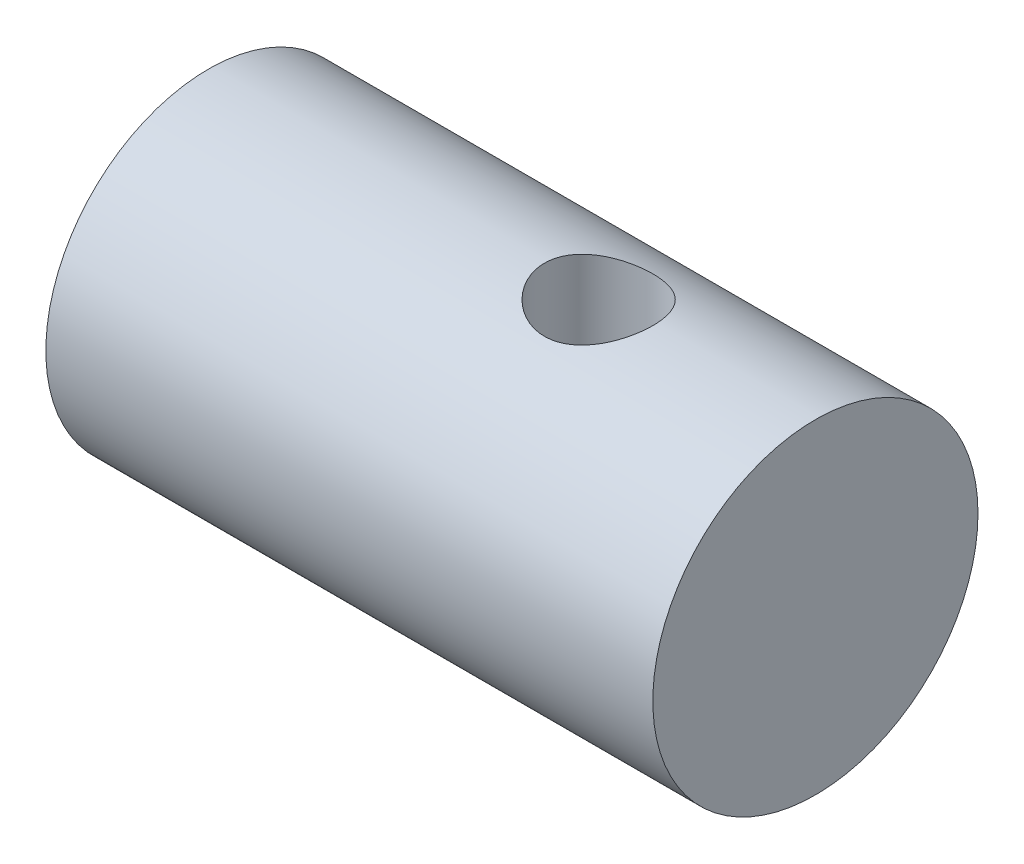
SolidWorks part; units mm, degrees
other "Preload Motor Output Shaft"
ref_plane "Front Plane" through (0, 0, 0) normal (0, 0, 1) x (1, 0, 0)
ref_plane "Top Plane" through (0, 0, 0) normal (0, 1, 0) x (1, 0, 0)
ref_plane "Right Plane" through (0, 0, 0) normal (1, 0, 0) x (0, 0, -1)
sketch3d "Finished shaft allocation sketch datum points"
  point P0 (-9.2, -29, -19.5)
  point P1 (-9.2, -19, -19.5)
  point P2 (-9.2, -29, -9.5)
ref_plane "Finished shaft allocation sketch plane" through (-9.2, 0, 0) normal (1, 0, 0) x (0, 0, -1)
sketch "Finished shaft allocation sketch" plane through (-9.2, 0, 0) normal (1, 0, 0) x (0, 0, -1)
  circle A0 centre (19.5, -29) radius 3
extrude "Finished shaft allocation" add sketch "Finished shaft allocation sketch" along normal blind 11.2 separate body
sketch3d "Coupling cross pin bore sketch datum points"
  point P0 (-2, -33, -19.5)
  point P1 (8, -33, -19.5)
  point P2 (-2, -33, -29.5)
ref_plane "Coupling cross pin bore sketch plane" through (0, -33, 0) normal (0, 1, 0) x (1, 0, 0)
sketch "Coupling cross pin bore sketch" plane through (0, -33, 0) normal (0, 1, 0) x (1, 0, 0)
  circle A0 centre (-2, 19.5) radius 1
extrude "Coupling cross pin bore" cut sketch "Coupling cross pin bore sketch" along normal blind 8
